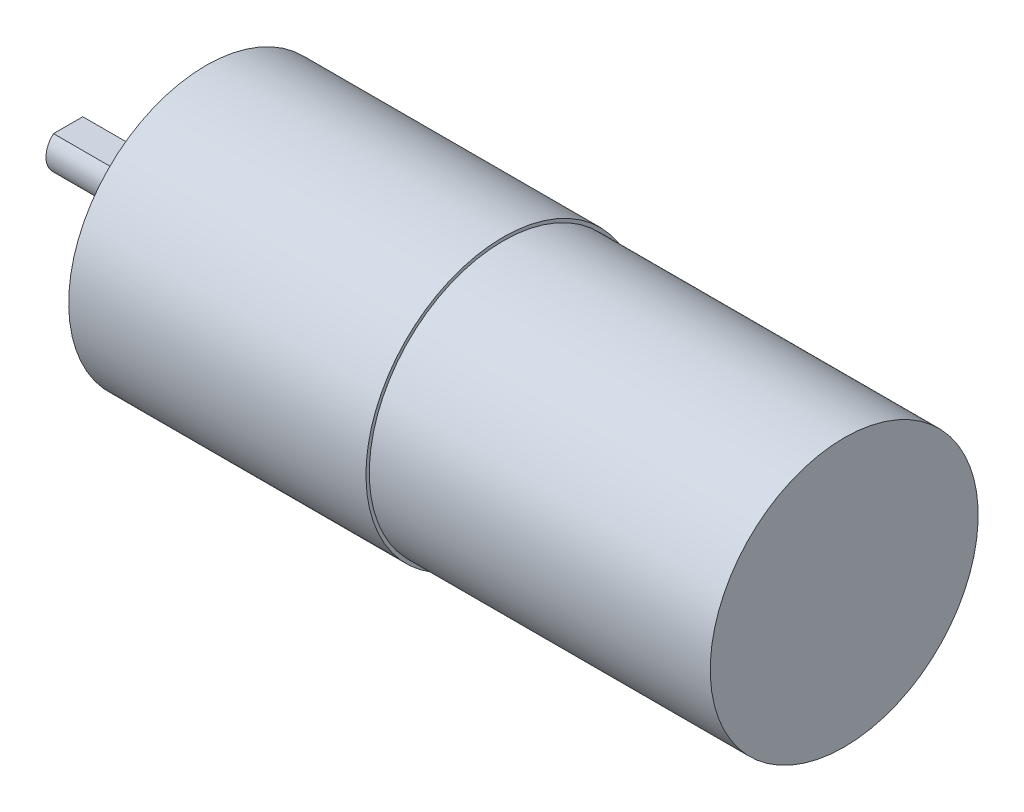
SolidWorks part; units mm, degrees
ref_plane "Front" through (0, 0, 0) normal (0, 0, 1) x (1, 0, 0)
ref_plane "Top" through (0, 0, 0) normal (0, 1, 0) x (1, 0, 0)
ref_plane "Right" through (0, 0, 0) normal (1, 0, 0) x (0, 0, -1)
sketch "Sketch1" plane through (0, 0, 0) normal (0, 0, 1) x (1, 0, 0)
  line L0 (0, 0) -> (-28.825, 0) construction
  line L1 (-15.4, 12.1) -> (15.4, 12.1)
  line L2 (-15.4, 12.1) -> (-15.4, -12.1)
  line L3 (-15.4, -12.1) -> (15.4, -12.1)
  line L4 (15.4, 12.1) -> (15.4, -12.1)
  line L5 (-15.4, 12.1) -> (15.4, -12.1) construction
  line L6 (-15.4, -12.1) -> (15.4, 12.1) construction
  line L7 (-28.825, 0) -> (-54.7, 0) construction
  line L8 (-42.25, 12.4) -> (-15.4, 12.4)
  line L9 (-42.25, 12.4) -> (-42.25, -12.4)
  line L10 (-42.25, -12.4) -> (-15.4, -12.4)
  line L11 (-15.4, 12.4) -> (-15.4, -12.4)
  line L12 (-42.25, 12.4) -> (-15.4, -12.4) construction
  line L13 (-42.25, -12.4) -> (-15.4, 12.4) construction
  line L14 (0, 0) -> (15.4, 0) construction
  line L15 (-44.8, 3.475) -> (-42.25, 3.475)
  line L16 (-44.8, 3.475) -> (-44.8, -3.475)
  line L17 (-44.8, -3.475) -> (-42.25, -3.475)
  line L18 (-42.25, 3.475) -> (-42.25, -3.475)
  line L19 (-44.8, 3.475) -> (-42.25, -3.475) construction
  line L20 (-44.8, -3.475) -> (-42.25, 3.475) construction
  line L22 (-54.7, 2) -> (-44.8, 2)
  line L23 (-54.7, 2) -> (-54.7, -2)
  line L24 (-54.7, -2) -> (-44.8, -2)
  line L25 (-44.8, 2) -> (-44.8, -2)
  line L26 (-54.7, 2) -> (-44.8, -2) construction
  line L27 (-54.7, -2) -> (-44.8, 2) construction
  point P0 (0, 0)
  point P12 (-43.525, 0)
  point P18 (-49.75, 0)
  dimension "D1" = 30.8
  dimension "D2" = 24.2
  dimension "D3" = 26.85
  dimension "D4" = 24.8
  dimension "D5" = 6.95
  dimension "D6" = 2.55
  dimension "D7" = 4
  dimension "D8" = 12.45
sketch "Sketch2" plane through (0, 0, 0) normal (0, 0, 1) x (1, 0, 0)
  line L0 (-42.25, 12.4) -> (-15.4, 12.4)
  line L1 (-15.4, 12.4) -> (-15.4, 12.1)
  line L2 (-15.4, 12.1) -> (15.4, -12.1) construction
  line L3 (-15.4, 12.1) -> (15.4, 12.1) construction
  line L4 (-15.4, 12.1) -> (15.4, 12.1)
  line L5 (-54.7, 0) -> (-54.7, 2)
  line L6 (-54.7, 2) -> (-44.8, 2)
  line L7 (-44.8, 2) -> (-44.8, 3.475)
  line L8 (-44.8, 3.475) -> (-42.25, 3.475)
  line L9 (-42.25, 3.475) -> (-42.25, 12.4)
  line L10 (-15.4, -12.1) -> (15.4, 12.1) construction
  line L11 (15.4, 12.1) -> (15.4, 0)
  line L12 (15.4, 0) -> (-54.7, 0)
revolve "Revolve3" add sketch "Sketch2" angle 360 about L7
sketch "Sketch3" plane through (-54.7, 0, 0) normal (-1, 0, 0) x (0, 0, 1)
  line L0 (-1.3229, 1.5) -> (1.3229, 1.5)
  line L1 (0, 1.5) -> (0, 2) construction
  circle A0 centre (0, 0) radius 2 construction
  arc A1 (1.3229, 1.5) -> (-1.3229, 1.5) centre (0, 0) ccw
  dimension "D1" = 0.5
extrude "Cut-Extrude1" cut sketch "Sketch3" against normal blind 8
